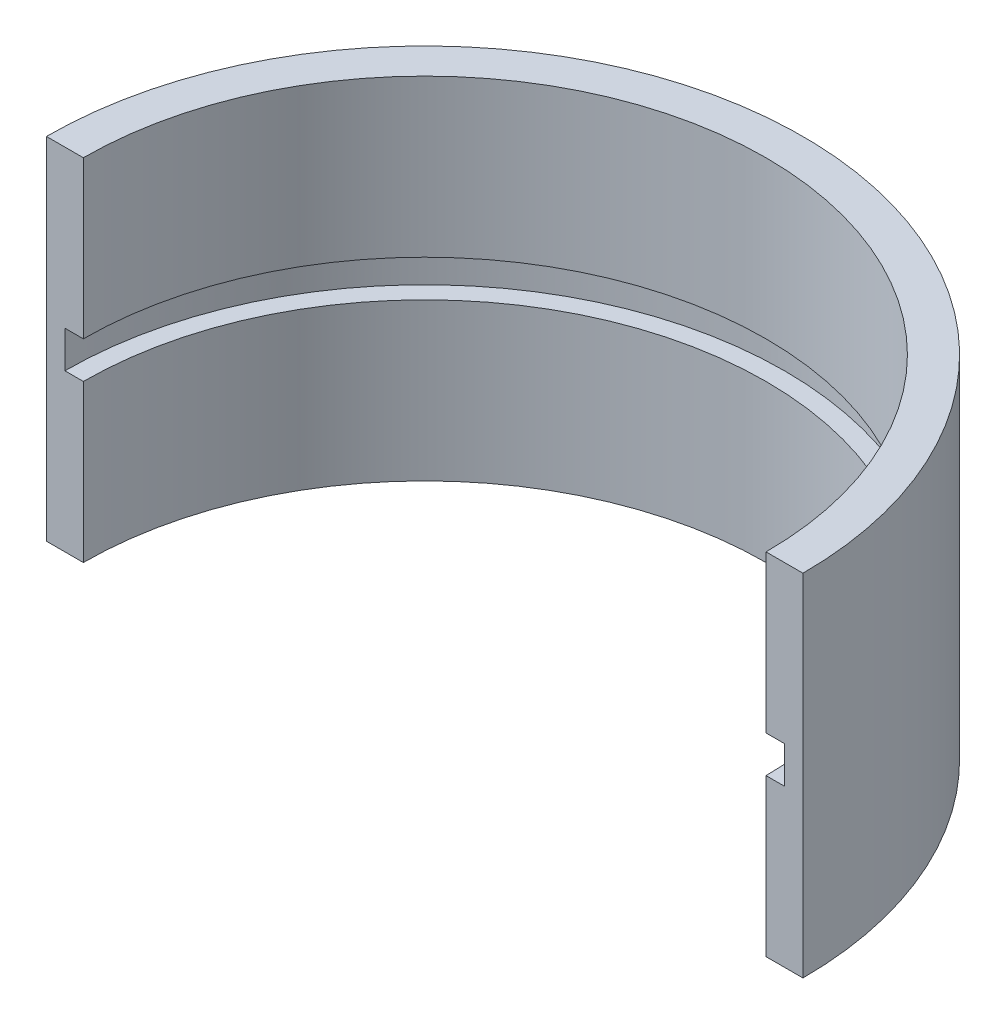
SolidWorks part; units mm, degrees
ref_plane "Front Plane" through (0, 0, 0) normal (0, 0, 1) x (1, 0, 0)
ref_plane "Top Plane" through (0, 0, 0) normal (0, 1, 0) x (1, 0, 0)
ref_plane "Right Plane" through (0, 0, 0) normal (1, 0, 0) x (0, 0, -1)
sketch "Sketch1" plane through (0, 0, 0) normal (0, 1, 0) x (1, 0, 0)
  line L0 (-20.5, 0) -> (20.5, 0)
  circle A0 centre (0, 0) radius 18.5
  circle A1 centre (0, 0) radius 20.5
  point P7 (0, 0)
  dimension "D1" = 37
  dimension "D2" = 41
extrude "Boss-Extrude1" add sketch "Sketch1" along normal blind 8.5 contours L0 A1 A0
sketch "Sketch2" plane through (0, 8.5, 0) normal (0, 1, 0) x (1, 0, 0)
  line L0 (-19.5, 0) -> (-20.5, 0)
  line L1 (19.5, 0) -> (20.5, 0)
  arc A2 (19.5, 0) -> (-19.5, 0) centre (0, 0) ccw
  arc A3 (19.5, 0) -> (-19.5, 0) centre (0, 0) ccw
  arc A5 (20.5, 0) -> (-20.5, 0) centre (0, 0) ccw
  arc A6 (20.5, 0) -> (-20.5, 0) centre (0, 0) ccw
  dimension "D1" = 1
  dimension "D2" = 0
extrude "Boss-Extrude2" add sketch "Sketch2" along normal blind 2
sketch "Sketch3" plane through (0, 10.5, 0) normal (0, 1, 0) x (1, 0, 0)
  line L0 (-20.5, 0) -> (-18.5, 0)
  line L1 (18.5, 0) -> (20.5, 0)
  arc A2 (18.5, 0) -> (-18.5, 0) centre (0, 0) ccw
  arc A3 (18.5, 0) -> (-18.5, 0) centre (0, 0) ccw
  arc A5 (20.5, 0) -> (-20.5, 0) centre (0, 0) ccw
  arc A6 (20.5, 0) -> (-20.5, 0) centre (0, 0) ccw
  dimension "D1" = 2
  dimension "D2" = 0
extrude "Boss-Extrude3" add sketch "Sketch3" along normal blind 8.5
